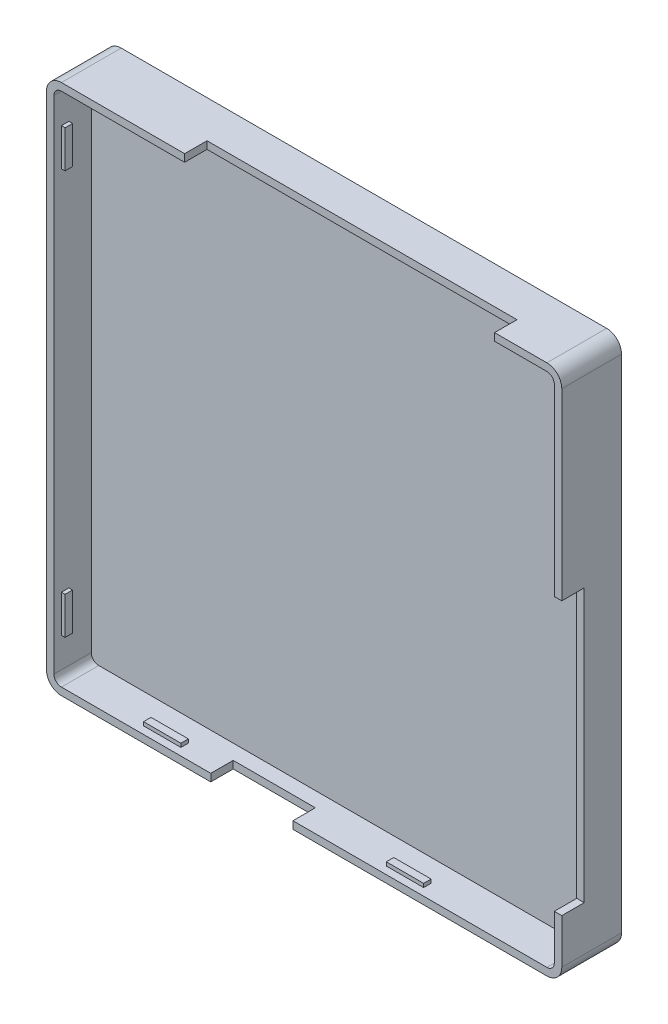
SolidWorks part; units mm, degrees
ref_plane "Plan de face" through (0, 0, 0) normal (0, 0, 1) x (1, 0, 0)
ref_plane "Plan de dessus" through (0, 0, 0) normal (0, 1, 0) x (1, 0, 0)
ref_plane "Plan de droite" through (0, 0, 0) normal (1, 0, 0) x (0, 0, -1)
sketch "Esquisse1" plane through (0, 0, 0) normal (0, 0, 1) x (1, 0, 0)
  line L1 (2, 0) -> (67, 0)
  line L2 (0, 2) -> (0, 69.1)
  line L3 (2, 71.1) -> (67, 71.1)
  line L4 (69, 2) -> (69, 69.1)
  arc A0 (2, 0) -> (0, 2) centre (2, 2) cw
  arc A1 (67, 0) -> (69, 2) centre (67, 2) ccw
  arc A2 (67, 71.1) -> (69, 69.1) centre (67, 69.1) cw
  arc A3 (0, 69.1) -> (2, 71.1) centre (2, 69.1) cw
  point P7 (0, 0)
  point P10 (69, 0)
  point P15 (0, 71.1)
  dimension "D3" = 2
  dimension "D1" = 71.1
  dimension "D2" = 69
extrude "Boss.-Extru.1" add sketch "Esquisse1" along normal blind 8
sketch "Esquisse3" plane through (0, 0, 8) normal (0, 0, 1) x (1, 0, 0)
  line L8 (2, 1) -> (67, 1)
  line L9 (68, 2) -> (68, 69.1)
  line L10 (67, 70.1) -> (2, 70.1)
  line L11 (1, 69.1) -> (1, 2)
  line L12 (2, 1) -> (67, 1)
  line L13 (68, 2) -> (68, 69.1)
  line L14 (67, 70.1) -> (2, 70.1)
  line L15 (1, 69.1) -> (1, 2)
  arc A8 (1, 2) -> (2, 1) centre (2, 2) ccw
  arc A9 (67, 1) -> (68, 2) centre (67, 2) ccw
  arc A10 (68, 69.1) -> (67, 70.1) centre (67, 69.1) ccw
  arc A11 (2, 70.1) -> (1, 69.1) centre (2, 69.1) ccw
  arc A12 (1, 2) -> (2, 1) centre (2, 2) ccw
  arc A13 (67, 1) -> (68, 2) centre (67, 2) ccw
  arc A14 (68, 69.1) -> (67, 70.1) centre (67, 69.1) ccw
  arc A15 (2, 70.1) -> (1, 69.1) centre (2, 69.1) ccw
  dimension "D1" = 1
extrude "Enlèv. mat.-Extru.1" cut sketch "Esquisse3" against normal blind 5
sketch "Esquisse4" plane through (0, 70.1, 0) normal (0, -1, 0) x (1, 0, 0)
  line L0 (67, 3) -> (2, 3) construction
  line L1 (8.1797, 6) -> (13.1797, 6)
  line L2 (8.1797, 6) -> (8.1797, 7)
  line L3 (8.1797, 7) -> (13.1797, 7)
  line L4 (13.1797, 6) -> (13.1797, 7)
  dimension "D1" = 3
  dimension "D2" = 1
  dimension "D3" = 5
extrude "Boss.-Extru.3" add sketch "Esquisse4" along normal blind 0.489 contours L1 L4 L3 L2
sketch "Esquisse5" plane through (68, 0, 0) normal (-1, 0, 0) x (0, 0, 1)
  line L0 (3, 2) -> (3, 69.1) construction
  line L1 (6, 66.1) -> (7, 66.1)
  line L2 (6, 66.1) -> (6, 61.1)
  line L3 (6, 61.1) -> (7, 61.1)
  line L4 (7, 66.1) -> (7, 61.1)
  line L5 (3, 69.1) -> (8, 69.1) construction
  dimension "D1" = 1
  dimension "D2" = 5
  dimension "D3" = 3
  dimension "D4" = 3
extrude "Boss.-Extru.4" add sketch "Esquisse5" along normal blind 0.489
sketch "Esquisse6" plane through (1, 0, 0) normal (1, 0, 0) x (0, 0, -1)
  line L0 (-3, 69.1) -> (-8, 69.1) construction
  line L1 (-6, 65.1) -> (-7, 65.1)
  line L2 (-6, 65.1) -> (-6, 60.1)
  line L3 (-6, 60.1) -> (-7, 60.1)
  line L4 (-7, 65.1) -> (-7, 60.1)
  line L5 (-3, 69.1) -> (-3, 2) construction
  dimension "D1" = 1
  dimension "D2" = 5
  dimension "D3" = 4
  dimension "D4" = 3
extrude "Boss.-Extru.5" add sketch "Esquisse6" along normal blind 0.489
sketch "Esquisse7" plane through (1, 0, 0) normal (1, 0, 0) x (0, 0, -1)
  line L0 (-3, 69.1) -> (-3, 2) construction
  line L1 (-6, 6) -> (-7, 6)
  line L2 (-6, 6) -> (-6, 11)
  line L3 (-6, 11) -> (-7, 11)
  line L4 (-7, 6) -> (-7, 11)
  line L5 (-3, 2) -> (-8, 2) construction
  dimension "D1" = 5
  dimension "D2" = 1
  dimension "D3" = 3
  dimension "D4" = 4
extrude "Boss.-Extru.6" add sketch "Esquisse7" along normal blind 0.489
sketch "Esquisse8" plane through (0, 1, 0) normal (0, 1, 0) x (1, 0, 0)
  line L0 (2, -3) -> (67, -3) construction
  line L1 (12, -6) -> (17, -6)
  line L2 (12, -6) -> (12, -7)
  line L3 (12, -7) -> (17, -7)
  line L4 (17, -6) -> (17, -7)
  line L5 (2, -3) -> (2, -8) construction
  point P6 (12, -6.5)
  dimension "D1" = 1
  dimension "D2" = 5
  dimension "D3" = 3
  dimension "D4" = 10
extrude "Boss.-Extru.7" add sketch "Esquisse8" along normal blind 0.489
sketch "Esquisse9" plane through (0, 1, 0) normal (0, 1, 0) x (1, 0, 0)
  line L0 (2, -3) -> (67, -3) construction
  line L1 (49.5, -6) -> (44.5, -6)
  line L2 (49.5, -6) -> (49.5, -7)
  line L3 (49.5, -7) -> (44.5, -7)
  line L4 (44.5, -6) -> (44.5, -7)
  line L5 (67, -3) -> (67, -8) construction
  dimension "D1" = 5
  dimension "D2" = 1
  dimension "D3" = 3
  dimension "D4" = 17.5
extrude "Boss.-Extru.8" add sketch "Esquisse9" along normal blind 0.489
sketch "Esquisse10" plane through (68, 0, 0) normal (-1, 0, 0) x (0, 0, 1)
  line L0 (3, 2) -> (8, 2) construction
  line L1 (5, 8) -> (8, 8)
  line L2 (5, 8) -> (5, 44.5)
  line L3 (5, 44.5) -> (8, 44.5)
  line L4 (8, 8) -> (8, 44.5)
  line L5 (3, 2) -> (3, 69.1) construction
  dimension "D1" = 36.5
  dimension "D2" = 6
  dimension "D3" = 3
  dimension "D4" = 2
extrude "Enlèv. mat.-Extru.3" cut sketch "Esquisse10" against normal through all contours L2 L1 L4 L3
sketch "Esquisse11" plane through (0, 70.1, 0) normal (0, -1, 0) x (1, 0, 0)
  line L0 (67, 3) -> (67, 8) construction
  line L1 (60, 5) -> (18.5, 5)
  line L2 (60, 5) -> (60, 8)
  line L3 (60, 8) -> (18.5, 8)
  line L4 (18.5, 5) -> (18.5, 8)
  line L5 (67, 3) -> (2, 3) construction
  dimension "D1" = 7
  dimension "D2" = 41.5
  dimension "D3" = 3
  dimension "D4" = 2
extrude "Enlèv. mat.-Extru.4" cut sketch "Esquisse11" against normal through all
sketch "Esquisse12" plane through (0, 1, 0) normal (0, 1, 0) x (1, 0, 0)
  line L0 (2, -3) -> (2, -8) construction
  line L1 (22, -5) -> (33, -5)
  line L2 (22, -5) -> (22, -8)
  line L3 (22, -8) -> (33, -8)
  line L4 (33, -5) -> (33, -8)
  line L5 (2, -3) -> (67, -3) construction
  dimension "D1" = 11
  dimension "D2" = 20
  dimension "D3" = 3
  dimension "D4" = 2
extrude "Enlèv. mat.-Extru.5" cut sketch "Esquisse12" against normal through all
ref_plane "Plan3" through (2, 1, 3) normal (1, 0, 0) x (0, 0, -1)
